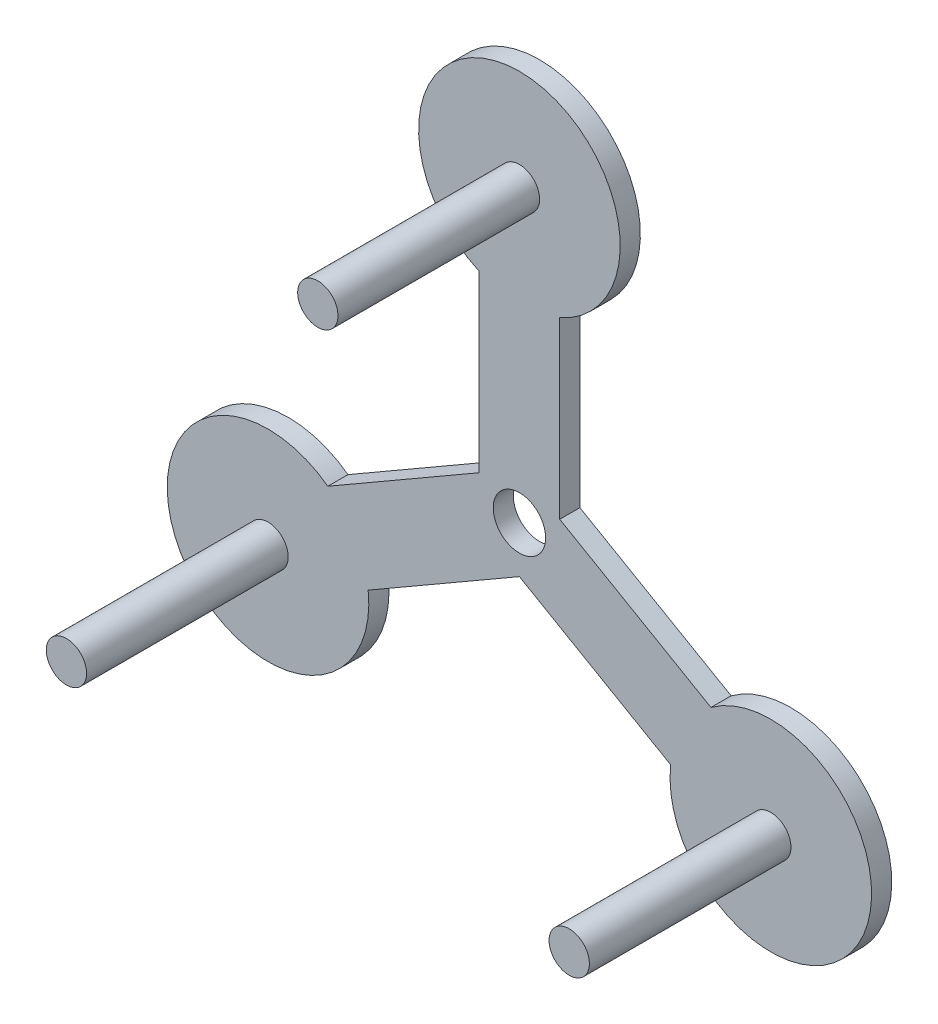
SolidWorks part; units mm, degrees
ref_plane "Front Plane" through (0, 0, 0) normal (0, 0, 1) x (1, 0, 0)
ref_plane "Top Plane" through (0, 0, 0) normal (0, 1, 0) x (1, 0, 0)
ref_plane "Right Plane" through (0, 0, 0) normal (1, 0, 0) x (0, 0, -1)
sketch "Sketch1" plane through (0, 0, 0) normal (0, 0, 1) x (1, 0, 0)
  line L0 (0, 0) -> (0, 144) construction
  line L1 (20, 144) -> (-20, 144)
  line L6 (0, 0) -> (124.7077, -72) construction
  line L7 (0, 0) -> (-124.7077, -72) construction
  line L8 (114.7077, -89.3205) -> (134.7077, -54.6795)
  line L9 (-114.7077, -89.3205) -> (-134.7077, -54.6795)
  line L10 (-134.7077, -54.6795) -> (-20, 11.547)
  line L11 (-20, 11.547) -> (-20, 144)
  line L12 (20, 144) -> (20, 11.547)
  line L13 (20, 11.547) -> (134.7077, -54.6795)
  line L14 (114.7077, -89.3205) -> (0, -23.094)
  line L15 (0, -23.094) -> (-114.7077, -89.3205)
  point P6 (0, 144)
  point P10 (0, 0)
  point P12 (124.7077, -72)
  point P15 (-124.7077, -72)
  dimension "D1" = 3
extrude "Boss-Extrude2" add sketch "Sketch1" along normal blind 10
sketch "Sketch3" plane through (0, 0, 10) normal (0, 0, 1) x (1, 0, 0)
  line L0 (-134.7077, -54.6795) -> (-114.7077, -89.3205) construction
  circle A0 centre (-124.7077, -72) radius 50
  circle A1 centre (0, 144) radius 50
  circle A2 centre (124.7077, -72) radius 50
  point P11 (0, 0)
  dimension "D1" = 3
extrude "Boss-Extrude3" add sketch "Sketch3" against normal blind 10
sketch "Sketch4" plane through (0, 0, 10) normal (0, 0, 1) x (1, 0, 0)
  circle A1 centre (0, 144) radius 10
  circle A2 centre (124.7077, -72) radius 10
  circle A3 centre (-124.7077, -72) radius 10
  point P9 (0, 0)
  dimension "D1" = 3
extrude "Boss-Extrude4" add sketch "Sketch4" along normal blind 90
sketch "Sketch5" plane through (0, 0, 100) normal (0, 0, 1) x (1, 0, 0)
  circle A0 centre (0, 144) radius 10
extrude "Cut-Extrude1" cut sketch "Sketch5" against normal blind 30
sketch "Sketch6" plane through (0, 0, 10) normal (0, 0, 1) x (1, 0, 0)
  circle A0 centre (0, 0) radius 13
extrude "Cut-Extrude2" cut sketch "Sketch6" against normal blind 10
sketch "Sketch7" plane through (0, 0, 70) normal (0, 0, 1) x (1, 0, 0)
  circle A0 centre (0, 144) radius 10
extrude "Boss-Extrude5" add sketch "Sketch7" along normal blind 30
sketch "Sketch9" plane through (0, 0, 100) normal (0, 0, 1) x (1, 0, 0)
  circle A0 centre (0, 144) radius 10
extrude "Boss-Extrude6" add sketch "Sketch9" along normal blind 10
sketch "Sketch10" plane through (0, 0, 100) normal (0, 0, 1) x (1, 0, 0)
  circle A0 centre (-124.7077, -72) radius 10
extrude "Boss-Extrude7" add sketch "Sketch10" along normal blind 10
sketch "Sketch11" plane through (0, 0, 100) normal (0, 0, 1) x (1, 0, 0)
  circle A0 centre (124.7077, -72) radius 10
extrude "Boss-Extrude8" add sketch "Sketch11" along normal blind 10
